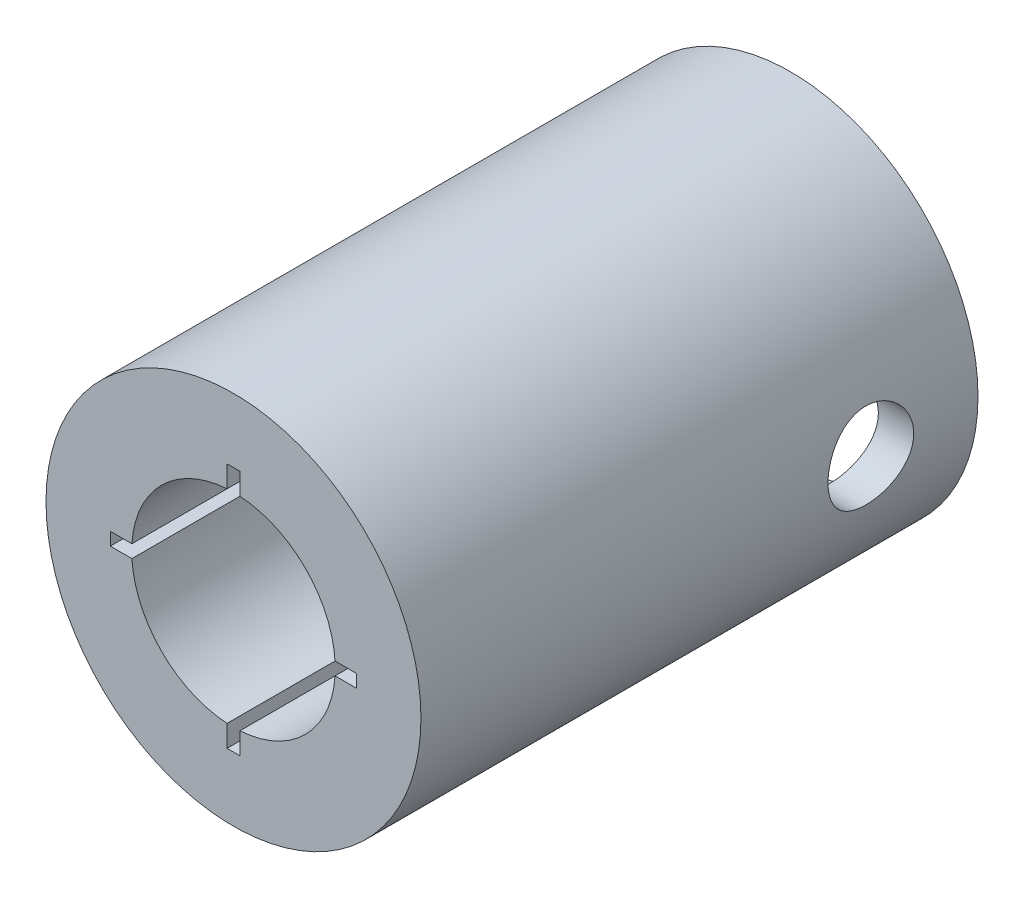
SolidWorks part; units mm, degrees
ref_plane "前视基准面" through (0, 0, 0) normal (0, 0, 1) x (1, 0, 0)
ref_plane "上视基准面" through (0, 0, 0) normal (0, 1, 0) x (1, 0, 0)
ref_plane "右视基准面" through (0, 0, 0) normal (1, 0, 0) x (0, 0, -1)
sketch "草图1" plane through (0, 0, 0) normal (0, 0, 1) x (1, 0, 0)
  circle A0 centre (0, 0) radius 7.1
  circle A1 centre (0, 0) radius 8.75
  dimension "D1" = 14.2
  dimension "D2" = 17.5
extrude "凸台-拉伸1" add sketch "草图1" along normal blind 10
sketch "草图2" plane through (0, 0, 0) normal (1, 0, 0) x (0, 0, -1)
  line L0 (-10, 8.75) -> (-10, -8.75) construction
  line L1 (0, 8.75) -> (-10, 8.75) construction
  circle A0 centre (-5, 0) radius 2
  dimension "D1" = 4
  dimension "D2" = 5
  dimension "D3" = 8.75
extrude "切除-拉伸1" cut sketch "草图2" along normal blind 20 and the other way blind 10
sketch "草图3" plane through (0, 0, 10) normal (0, 0, 1) x (1, 0, 0)
  circle A0 centre (0, 0) radius 4.75
  circle A1 centre (0, 0) radius 8.75
  dimension "D1" = 9.5
  dimension "D2" = 17.5
extrude "凸台-拉伸2" add sketch "草图3" along normal blind 16
sketch "草图4" plane through (0, 0, 26) normal (0, 0, 1) x (1, 0, 0)
  line L0 (0, 0) -> (0, -4.75) construction
  line L1 (-4.75, 0) -> (4.75, 0) construction
  line L2 (-0.3, -4.7405) -> (-0.3, -5.75)
  line L3 (-0.3, -5.75) -> (0.3, -5.75)
  line L4 (0.3, -5.75) -> (0.3, -4.7405)
  line L5 (-5.75, -0.3) -> (-4.7405, -0.3)
  line L6 (-4.7405, 0.3) -> (-5.75, 0.3)
  line L7 (-5.75, 0.3) -> (-5.75, -0.3)
  line L8 (-0.3, 5.75) -> (-0.3, 4.7405)
  line L9 (0.3, 4.7405) -> (0.3, 5.75)
  line L10 (0.3, 5.75) -> (-0.3, 5.75)
  line L11 (5.75, 0.3) -> (4.7405, 0.3)
  line L12 (4.7405, -0.3) -> (5.75, -0.3)
  line L13 (5.75, -0.3) -> (5.75, 0.3)
  circle A0 centre (0, 0) radius 4.75 construction
  arc A1 (-0.3, -4.7405) -> (0.3, -4.7405) centre (0, 0) ccw
  arc A2 (-4.7405, 0.3) -> (-4.7405, -0.3) centre (0, 0) ccw
  arc A3 (0.3, 4.7405) -> (-0.3, 4.7405) centre (0, 0) ccw
  arc A4 (4.7405, -0.3) -> (4.7405, 0.3) centre (0, 0) ccw
  point P26 (0, 0)
  dimension "D1" = 0.6
  dimension "D2" = 0.3
  dimension "D3" = 11.5
  dimension "D4" = 4
extrude "切除-拉伸2" cut sketch "草图4" against normal blind 8
